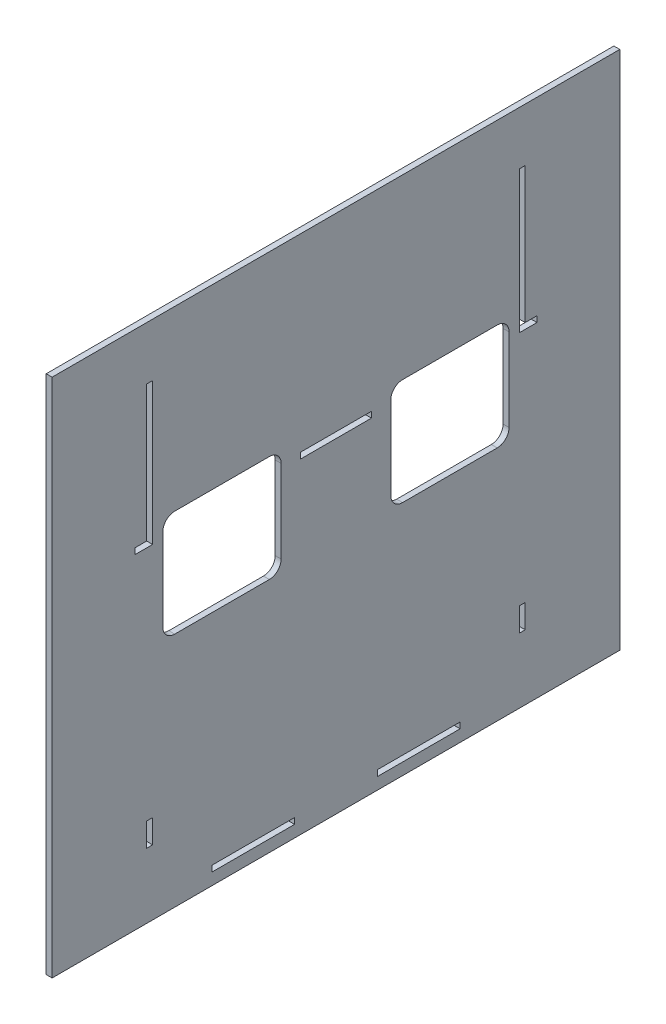
SolidWorks part; units mm, degrees
ref_plane "Front Plane" through (0, 0, 0) normal (0, 0, 1) x (1, 0, 0)
ref_plane "Top Plane" through (0, 0, 0) normal (0, 1, 0) x (1, 0, 0)
ref_plane "Right Plane" through (0, 0, 0) normal (1, 0, 0) x (0, 0, -1)
sketch "Sketch1" plane through (0, 0, 0) normal (1, 0, 0) x (0, 0, -1)
  line L1 (-304.8, -279.4) -> (304.8, -279.4)
  line L2 (-304.8, -279.4) -> (-304.8, 279.4)
  line L3 (-304.8, 279.4) -> (304.8, 279.4)
  line L4 (304.8, -279.4) -> (304.8, 279.4)
  line L5 (-304.8, -279.4) -> (304.8, 279.4) construction
  line L6 (-304.8, 279.4) -> (304.8, -279.4) construction
  point P0 (0, 0)
  point P6 (0, 0)
  dimension "D1" = 609.6
  dimension "D2" = 558.8
extrude "Main Body" add sketch "Sketch1" along normal blind 6.35
sketch "Sketch2" plane through (6.35, 0, 0) normal (1, 0, 0) x (0, 0, -1)
  line L5 (304.8, 279.4) -> (-304.8, 279.4) construction
  line L6 (-203.2, 222.25) -> (-196.85, 222.25)
  line L7 (-203.2, 222.25) -> (-203.2, 69.85)
  line L16 (-203.2, 69.85) -> (-196.85, 69.85)
  line L22 (-196.85, 222.25) -> (-196.85, 69.85)
  line L64 (196.85, 222.25) -> (203.2, 222.25)
  line L65 (196.85, 222.25) -> (196.85, 69.85)
  line L89 (196.85, 69.85) -> (203.2, 69.85)
  line L90 (203.2, 222.25) -> (203.2, 69.85)
  dimension "D1" = 6.35
  dimension "D2" = 57.15
  dimension "D3" = 152.4
  dimension "D4" = 196.85
  dimension "D5" = 196.85
extrude "Cut-Extrude1" cut sketch "Sketch2" against normal through all
sketch "Sketch8" plane through (6.35, 0, 0) normal (1, 0, 0) x (0, 0, -1)
  line L0 (304.8, 279.4) -> (-304.8, 279.4) construction
  line L1 (-185.8597, 88.9) -> (-58.8597, 88.9)
  line L2 (-185.8597, 88.9) -> (-185.8597, -25.4)
  line L3 (-185.8597, -25.4) -> (-58.8597, -25.4)
  line L4 (-58.8597, 88.9) -> (-58.8597, -25.4)
  line L5 (-185.8597, 88.9) -> (-58.8597, -25.4) construction
  line L6 (-185.8597, -25.4) -> (-58.8597, 88.9) construction
  point P0 (-122.3597, 31.75)
  dimension "D1" = 127
  dimension "D2" = 114.3
  dimension "D3" = 185.8597
  dimension "D4" = 190.5
extrude "Cut-Extrude5" cut sketch "Sketch8" against normal through all
fillet "Fillet3" radius 12.7 4 edges at (3.175, -25.4, 58.8597) (3.175, -25.4, 185.8597) (3.175, 88.9, 58.8597) (3.175, 88.9, 185.8597)
mirror "Mirror3" about plane through (0, 0, 0) normal (0, 0, 1) of "Fillet3", "Cut-Extrude5"
sketch "Sketch9" plane through (6.35, 0, 0) normal (1, 0, 0) x (0, 0, -1)
  line L65 (-304.8, -279.4) -> (304.8, -279.4) construction
  line L66 (-133.35, -260.35) -> (-44.45, -260.35)
  line L67 (-133.35, -260.35) -> (-133.35, -266.7)
  line L68 (-133.35, -266.7) -> (-44.45, -266.7)
  line L69 (-44.45, -260.35) -> (-44.45, -266.7)
  dimension "D1" = 88.9
  dimension "D2" = 6.35
  dimension "D3" = 12.7
  dimension "D4" = 44.45
extrude "Cut-Extrude7" cut sketch "Sketch9" against normal through all
mirror "Mirror4" about plane through (0, 0, 0) normal (0, 0, 1) of "Cut-Extrude7"
sketch "Sketch10" plane through (6.35, 0, 0) normal (1, 0, 0) x (0, 0, -1)
  line L0 (-196.85, 69.85) -> (-196.85, 222.25) construction
  line L1 (-203.2, -184.15) -> (-196.85, -184.15)
  line L2 (-203.2, -184.15) -> (-203.2, -209.55)
  line L3 (-203.2, -209.55) -> (-196.85, -209.55)
  line L4 (-196.85, -184.15) -> (-196.85, -209.55)
  line L6 (203.2, 69.85) -> (203.2, 222.25) construction
  line L7 (196.85, -184.15) -> (203.2, -184.15)
  line L8 (196.85, -184.15) -> (196.85, -209.55)
  line L9 (196.85, -209.55) -> (203.2, -209.55)
  line L10 (203.2, -184.15) -> (203.2, -209.55)
  line L11 (196.85, 222.25) -> (196.85, 69.85) construction
  line L12 (-304.8, -279.4) -> (304.8, -279.4) construction
  dimension "D1" = 25.4
  dimension "D2" = 6.35
  dimension "D3" = 69.85
extrude "Cut-Extrude8" cut sketch "Sketch10" against normal through all
sketch "Sketch11" plane through (6.35, 0, 0) normal (1, 0, 0) x (0, 0, -1)
  line L0 (-203.2, 222.25) -> (-203.2, 69.85) construction
  line L1 (-203.2, 76.2) -> (-215.9, 76.2)
  line L2 (-203.2, 76.2) -> (-203.2, 69.85)
  line L3 (-203.2, 69.85) -> (-215.9, 69.85)
  line L4 (-215.9, 76.2) -> (-215.9, 69.85)
  line L5 (-196.85, 222.25) -> (-203.2, 222.25) construction
  line L6 (203.2, 69.85) -> (203.2, 222.25) construction
  line L7 (203.2, 76.2) -> (215.9, 76.2)
  line L8 (203.2, 76.2) -> (203.2, 69.85)
  line L9 (203.2, 69.85) -> (215.9, 69.85)
  line L10 (215.9, 76.2) -> (215.9, 69.85)
  dimension "D1" = 6.35
  dimension "D2" = 12.7
  dimension "D3" = 146.05
  dimension "D4" = 6.35
  dimension "D5" = 12.7
extrude "Cut-Extrude9" cut sketch "Sketch11" against normal through all
sketch "Sketch12" plane through (6.35, 0, 0) normal (1, 0, 0) x (0, 0, -1)
  line L0 (215.9, 76.2) -> (203.2, 76.2) construction
  line L1 (-38.1, 76.2) -> (38.1, 76.2)
  line L2 (-38.1, 76.2) -> (-38.1, 69.85)
  line L3 (-38.1, 69.85) -> (38.1, 69.85)
  line L4 (38.1, 76.2) -> (38.1, 69.85)
  line L5 (196.85, 69.85) -> (215.9, 69.85) construction
  point P4 (0, 69.85)
  dimension "D1" = 76.2
extrude "Cut-Extrude10" cut sketch "Sketch12" against normal through all
sketch "Sketch13" [suppressed] plane through (6.35, 0, 0) normal (1, 0, 0) x (0, 0, -1)
  line L1 (-12.7, 76.2) -> (12.7, 76.2)
  line L2 (-12.7, 76.2) -> (-12.7, 118.8491)
  line L3 (-12.7, 118.8491) -> (12.7, 118.8491)
  line L4 (12.7, 76.2) -> (12.7, 118.8491)
  line L5 (38.1, 76.2) -> (-38.1, 76.2) construction
  line L6 (-12.7, 53.4505) -> (12.7, 53.4505)
  line L7 (-12.7, 53.4505) -> (-12.7, 69.85)
  line L8 (-12.7, 69.85) -> (12.7, 69.85)
  line L9 (12.7, 53.4505) -> (12.7, 69.85)
  line L10 (-38.1, 69.85) -> (38.1, 69.85) construction
  dimension "D1" = 25.4
  dimension "D2" = 25.4
  dimension "D3" = 42.6491
  dimension "D4" = 16.3995
extrude "Cut-Extrude11" [suppressed] cut sketch "Sketch13" against normal through all
